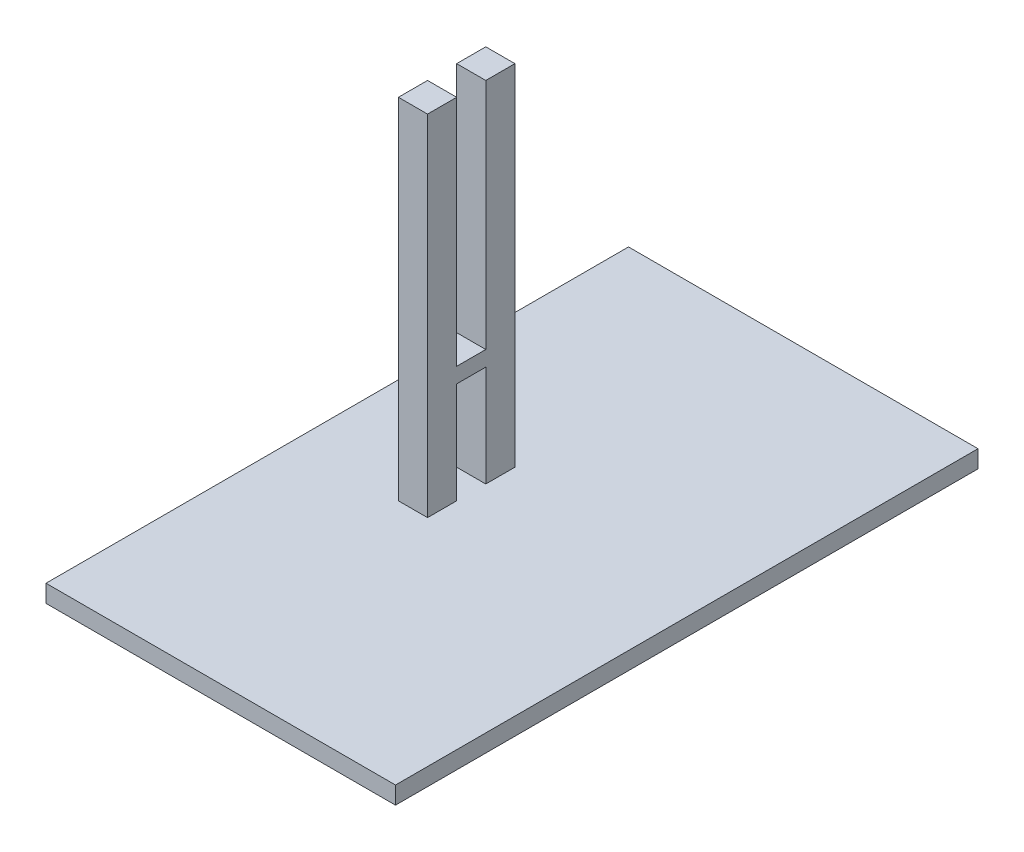
SolidWorks part; units mm, degrees
ref_plane "Front Plane" through (0, 0, 0) normal (0, 0, 1) x (1, 0, 0)
ref_plane "Top Plane" through (0, 0, 0) normal (0, 1, 0) x (1, 0, 0)
ref_plane "Right Plane" through (0, 0, 0) normal (1, 0, 0) x (0, 0, -1)
sketch "Sketch1" plane through (0, 0, 0) normal (0, 1, 0) x (1, 0, 0)
  line L1 (-30, 50) -> (30, 50)
  line L2 (-30, 50) -> (-30, -50)
  line L3 (-30, -50) -> (30, -50)
  line L4 (30, 50) -> (30, -50)
  line L5 (-30, 50) -> (30, -50) construction
  line L6 (-30, -50) -> (30, 50) construction
  point P1 (0, 0)
  dimension "D1" = 60
  dimension "D2" = 100
extrude "Boss-Extrude1" add sketch "Sketch1" along normal blind 3
sketch "Sketch2" plane through (0, 3, 0) normal (0, 1, 0) x (1, 0, 0)
  line L2 (-9.5, 2.5) -> (-7, 2.5)
  line L4 (-9.5, -2.5) -> (-7, -2.5)
  line L5 (-9.5, -2.5) -> (-12, -2.5)
  line L6 (-12, -2.5) -> (-12, -7.5)
  line L7 (-12, -7.5) -> (-7, -7.5)
  line L8 (-7, -7.5) -> (-7, -2.5)
  line L9 (-7, 7.5) -> (-7, 2.5)
  line L10 (-12, 7.5) -> (-7, 7.5)
  line L11 (-12, 2.5) -> (-12, 7.5)
  line L12 (-9.5, 2.5) -> (-12, 2.5)
  dimension "D4" = 2.5
  dimension "D5" = 2.5
  dimension "D6" = 5
extrude "Boss-Extrude2" add sketch "Sketch2" along normal blind 60
sketch "Sketch3" plane through (-7, 0, 0) normal (1, 0, 0) x (0, 0, -1)
  line L3 (-2.5, 63) -> (-2.5, 3) construction
  line L4 (-2.5, 23) -> (2.5, 23)
  line L5 (2.5, 63) -> (2.5, 3) construction
  line L6 (2.5, 23) -> (2.5, 20.3851)
  line L7 (2.5, 20.3851) -> (-2.5, 20.3851)
  line L8 (-2.5, 20.3851) -> (-2.5, 23)
extrude "Boss-Extrude3" add sketch "Sketch3" against normal up to vertex
